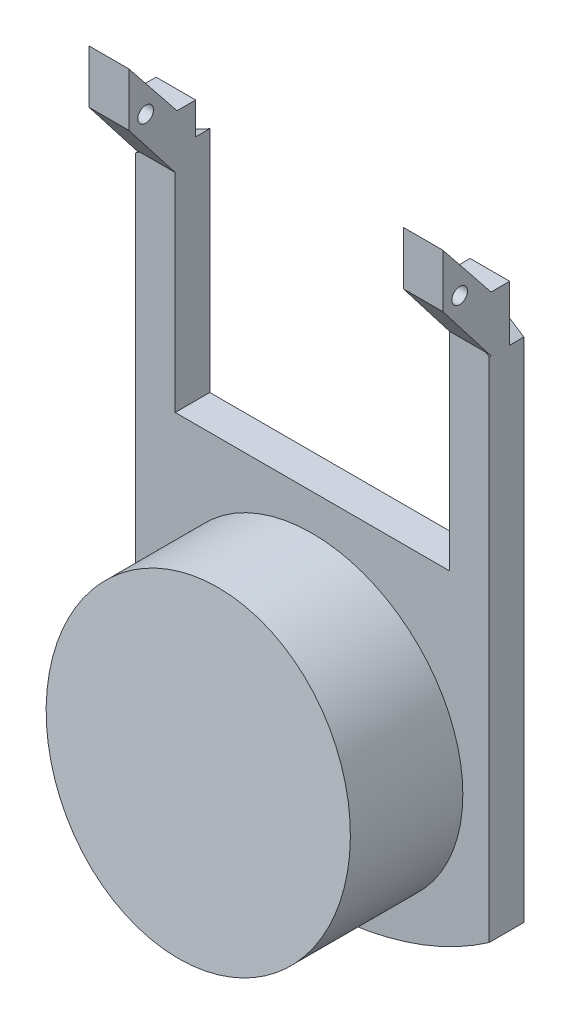
SolidWorks part; units mm, degrees
material "ABS"
ref_plane "X-Y Datum" through (0, 0, 0) normal (0, 0, 1) x (1, 0, 0)
ref_plane "X-Z Datum" through (0, 0, 0) normal (0, 1, 0) x (1, 0, 0)
ref_plane "Y-Z Datum" through (0, 0, 0) normal (1, 0, 0) x (0, 0, -1)
sketch "Sketch1" plane through (0, 0, 0) normal (0, 0, 1) x (1, 0, 0)
  line L0 (0, 34.4997) -> (0, 21.5457)
  line L2 (-4.064, 32.0939) -> (-4.064, -19.9922)
  line L4 (32.258, 32.0939) -> (32.258, -19.9922)
  line L6 (28.194, 21.5457) -> (28.194, 34.4997)
  line L7 (0, 21.5457) -> (0, 11.0322)
  line L9 (28.194, 11.0322) -> (28.194, 21.5457)
  line L11 (0, 11.0322) -> (28.194, 11.0322)
  arc A0 (-4.064, -19.9922) -> (32.258, -19.9922) centre (14.097, 6.0508) ccw
  arc A1 (32.258, 32.0939) -> (28.194, 34.4997) centre (14.097, 6.0508) ccw
  arc A2 (0, 34.4997) -> (-4.064, 32.0939) centre (14.097, 6.0508) ccw
  dimension "D3" = 63.5
  dimension "D1" = 4.064
  dimension "D2" = 4.064
extrude "Lid Profile" add sketch "Sketch1" along normal blind 3.556
sketch "Sketch2" plane through (0, 0, 3.556) normal (0, 0, 1) x (1, 0, 0)
  line L0 (14.097, -25.6992) -> (14.097, -23.6672) construction
  circle A0 centre (14.0542, -8.1732) radius 15.494
  arc A3 (-4.064, -19.9922) -> (32.258, -19.9922) centre (14.097, 6.0508) ccw construction
  dimension "D1" = 30.988
  dimension "D2" = 2.032
  dimension "D3" = 15.494
extrude "Mouthpiece Cover" add sketch "Sketch2" along normal blind 13.716
sketch "Sketch5" plane through (0, 0, 0) normal (0, 0, -1) x (-1, 0, 0)
  line L0 (-14.097, -25.6992) -> (-14.097, -23.6672) construction
  circle A0 centre (-14.097, -8.1732) radius 13.589
  arc A1 (-32.258, -19.9922) -> (4.064, -19.9922) centre (-14.097, 6.0508) ccw construction
  dimension "D3" = 27.178
  dimension "D1" = 2.032
  dimension "D2" = 15.494
extrude "Mouthpiece Inside" cut sketch "Sketch5" against normal blind 12.7
sketch "Sketch10" plane through (-4.064, 0, 0) normal (-1, 0, 0) x (0, 0, 1)
  line L1 (3.3658, 32.1382) -> (8.3213, 38.5154)
  line L2 (8.3213, 38.5154) -> (8.3213, 43.9842)
  line L3 (8.3213, 43.9842) -> (3.3658, 37.7823)
  line L4 (3.3658, 37.7823) -> (1.4551, 37.7823)
  line L5 (1.4551, 37.7823) -> (1.4551, 28.8976)
  line L6 (1.4551, 28.8976) -> (3.3658, 28.8976)
  line L7 (3.3658, 28.8976) -> (3.3658, 32.1382)
sketch "Sketch12" plane through (0, 0, 0) normal (1, 0, 0) x (0, 0, -1)
  line L0 (-3.556, 7.3208) -> (-17.272, 7.3208)
  line L1 (-17.272, 7.3208) -> (-17.272, -23.6672)
  line L2 (-17.272, -23.6672) -> (-3.556, -23.6672)
  line L3 (-3.556, -19.9922) -> (-3.556, -25.6992) construction
  line L4 (-3.556, -23.6672) -> (-3.556, 7.3208)
  line L5 (-3.556, 7.3208) -> (-13.208, 7.3208)
  line L6 (-13.208, 7.3208) -> (-17.272, -23.6672)
  dimension "D1" = 9.652
extrude "Mouthpiece Angled Cut" cut sketch "Sketch12" along normal mid plane 63.5 contours L6 L0 L1
extrude "Left Lid Handle " add sketch "Sketch10" against normal up to surface (4.064 mm away) up to face at (0, 22.766, 1.778)
sketch "Sketch14" plane through (28.194, 0, 0) normal (-1, 0, 0) x (0, 0, 1)
  line L0 (8.3213, 43.9842) -> (8.3213, 38.5154)
  line L1 (8.3213, 43.9842) -> (3.3658, 37.7823) construction
  line L2 (8.3213, 38.5154) -> (8.3213, 43.9842) construction
  line L3 (3.3658, 32.1382) -> (8.3213, 38.5154) construction
  line L4 (8.3213, 38.5154) -> (3.3658, 32.0939)
  line L5 (3.3658, 32.0939) -> (3.302, 26.6264)
  line L6 (3.302, 26.6264) -> (1.5362, 26.6264)
  line L7 (1.5362, 26.6264) -> (1.4551, 37.7823)
  line L8 (1.4551, 37.7823) -> (1.4551, 32.0939) construction
  line L9 (1.4551, 37.7823) -> (3.3658, 37.7823)
  line L10 (3.3658, 37.7823) -> (1.4551, 37.7823) construction
  line L11 (3.3658, 37.7823) -> (8.3213, 43.9842)
extrude "Right Lid Handle" add sketch "Sketch14" against normal up to surface (4.064 mm away) up to face at (32.258, 6.0508, 1.778)
sketch "Sketch15" plane through (-4.064, 0, 0) normal (-1, 0, 0) x (0, 0, 1)
  circle A0 centre (6.5869, 39.0827) radius 0.8033
extrude "Cut-Extrude1" cut sketch "Sketch15" against normal up to surface (36.322 mm away) up to face at (32.258, 24.6455, 3.3438)
